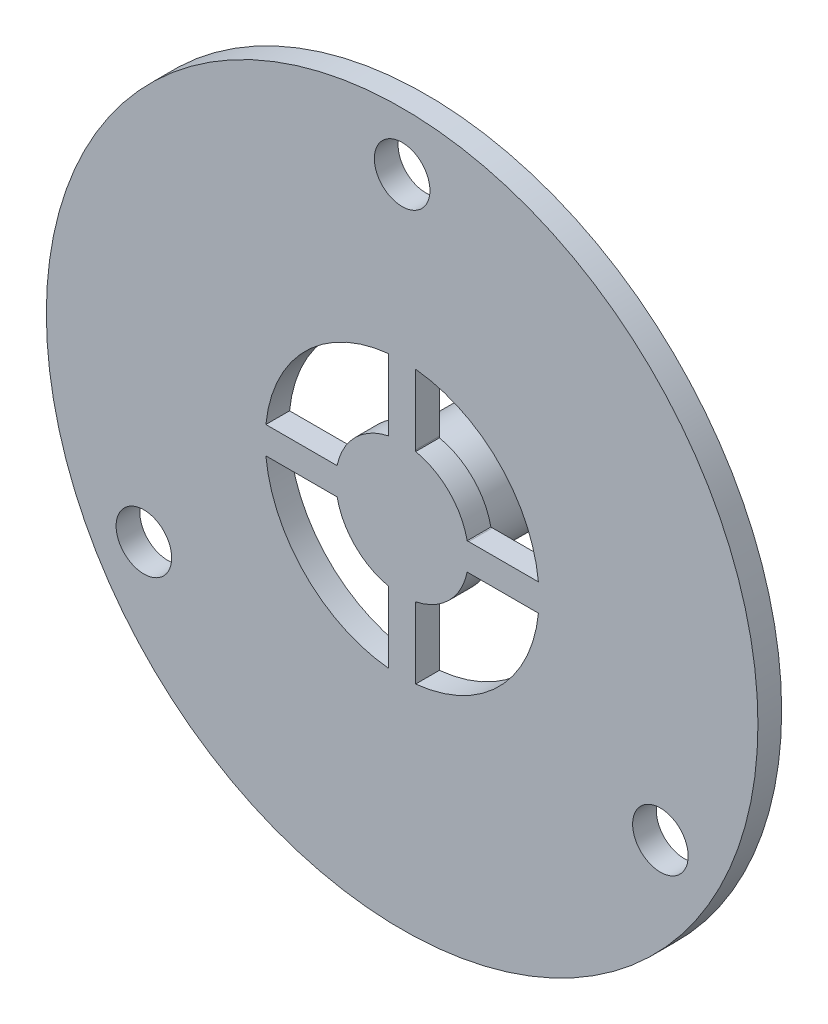
SolidWorks part; units mm, degrees
ref_plane "Front Plane" through (0, 0, 0) normal (0, 0, 1) x (1, 0, 0)
ref_plane "Top Plane" through (0, 0, 0) normal (0, 1, 0) x (1, 0, 0)
ref_plane "Right Plane" through (0, 0, 0) normal (1, 0, 0) x (0, 0, -1)
sketch "Model" plane through (0, 0, 0) normal (0, 0, 1) x (1, 0, 0)
  line L0 (17.5, -10.1036) -> (17.5, 10.1036)
  line L1 (17.5, 10.1036) -> (0, 20.2073)
  line L2 (0, 20.2073) -> (-17.5, 10.1036)
  line L3 (-17.5, -10.1036) -> (0, -20.2073)
  line L4 (0, -20.2073) -> (17.5, -10.1036)
  line L5 (-17.5, 10.1036) -> (-17.5, -10.1036)
  circle A0 centre (-38.1051, -22) radius 4.1
  circle A1 centre (38.1051, -22) radius 4.1
  circle A2 centre (0, 44) radius 4.1
  circle A3 centre (0, 0) radius 52.5
sketch "Sketch2" plane through (0, 0, 0) normal (0, 0, 1) x (1, 0, 0)
  line L0 (-17.5, 10.1036) -> (0, 20.2073)
  line L1 (0, 20.2073) -> (17.5, 10.1036)
  line L2 (17.5, 10.1036) -> (17.5, -10.1036)
  line L3 (17.5, -10.1036) -> (0, -20.2073)
  line L4 (0, -20.2073) -> (-17.5, -10.1036)
  line L5 (-17.5, -10.1036) -> (-17.5, 10.1036)
  circle A0 centre (0, 0) radius 52.5
  circle A1 centre (0, 44) radius 4.1
  circle A2 centre (38.1051, -22) radius 4.1
  circle A3 centre (-38.1051, -22) radius 4.1
extrude "Boss-Extrude1" add sketch "Sketch2" along normal blind 3.5
sketch "Sketch3" plane through (0, 0, 0) normal (0, 0, -1) x (-1, 0, 0)
  circle A0 centre (0, 0) radius 20.2073
extrude "Cut-Extrude1" cut sketch "Sketch3" against normal blind 11.8
sketch "Sketch4" plane through (0, 0, 0) normal (0, 0, -1) x (-1, 0, 0)
  line L0 (-9.8032, -0.001) -> (-34.4037, -0.001) construction
  line L3 (-9.8032, -0.001) -> (-9.8042, -0.001) construction
  line L4 (2, 9.8042) -> (2, 34.4047)
  line L5 (9.8052, -1.999) -> (34.4057, -1.999)
  line L6 (-1.998, -9.8042) -> (-1.998, -34.4047)
  line L7 (-9.8032, 1.999) -> (-34.4037, 1.999)
  line L8 (-2, 9.8042) -> (-2, 34.4047)
  line L9 (9.8052, 2.001) -> (34.4057, 2.001)
  line L10 (2.002, -9.8042) -> (2.002, -34.4047)
  line L11 (-9.8032, -2.001) -> (-34.4037, -2.001)
  line L12 (-9.8032, 1.999) -> (-9.5982, 1.999)
  line L13 (-9.8032, -2.001) -> (-9.5978, -2.001)
  line L14 (-2, 9.8042) -> (-2, 9.598)
  line L15 (2, 9.8042) -> (2, 9.598)
  line L16 (2.002, -9.5976) -> (2.002, -9.8042)
  line L17 (-1.998, -9.5984) -> (-1.998, -9.8042)
  line L18 (9.5978, 2.001) -> (9.8052, 2.001)
  line L19 (9.5982, -1.999) -> (9.8052, -1.999)
  line L20 (-34.4037, 1.999) -> (-34.4037, -2.001)
  line L21 (2.002, -34.4047) -> (-1.998, -34.4047)
  line L22 (34.4057, 2.001) -> (34.4057, -1.999)
  line L23 (2, 34.4047) -> (-2, 34.4047)
  arc A0 (-2, 9.598) -> (-9.5982, 1.999) centre (0, 0) ccw
  arc A1 (9.5978, 2.001) -> (2, 9.598) centre (0, 0) ccw
  arc A2 (2.002, -9.5976) -> (9.5982, -1.999) centre (0, 0) ccw
  arc A3 (-9.5978, -2.001) -> (-1.998, -9.5984) centre (0, 0) ccw
  point P6 (0, 0)
  point P11 (0.001, 0.001)
  point P14 (0.002, 0)
  point P17 (0.001, -0.001)
  point P18 (0.001, 0)
  dimension "D2" = 2
  dimension "D3" = 2
  dimension "D1" = 4
extrude "Boss-Extrude2" add sketch "Sketch4" against normal up to surface (3.5 mm away) up to face at (20.2073, 0, 3.5)
sketch "Sketch5" plane through (0, 0, 0) normal (0, 0, -1) x (-1, 0, 0)
  line L1 (0, 2.6) -> (3.4249, 2.6)
  line L2 (3.4249, 2.6) -> (-3.4249, 2.6)
  circle A0 centre (0, 0) radius 7.7818
  circle A1 centre (0, 0) radius 4.3
  dimension "D1" = 8.6
extrude "Boss-Extrude3" add sketch "Sketch5" along normal blind 11.8 contours A0 A1 | L1 A1 L2
